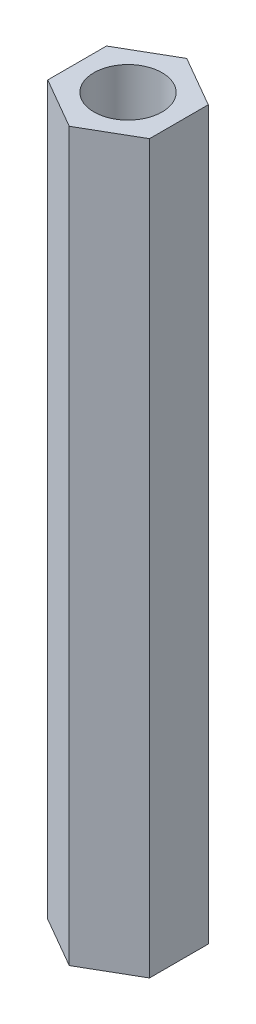
SolidWorks part; units mm, degrees
ref_plane "Front Plane" through (0, 0, 0) normal (0, 0, 1) x (1, 0, 0)
ref_plane "Top Plane" through (0, 0, 0) normal (0, 1, 0) x (1, 0, 0)
ref_plane "Right Plane" through (0, 0, 0) normal (1, 0, 0) x (0, 0, -1)
sketch "Sketch1" plane through (0, 0, 0) normal (0, 1, 0) x (1, 0, 0)
  line L1 (0, -2.0531) -> (1.778, -1.0265)
  line L2 (1.778, -1.0265) -> (1.778, 1.0265)
  line L3 (1.778, 1.0265) -> (0, 2.0531)
  line L4 (0, 2.0531) -> (-1.778, 1.0265)
  line L5 (-1.778, 1.0265) -> (-1.778, -1.0265)
  line L6 (-1.778, -1.0265) -> (0, -2.0531)
  circle A0 centre (0, 0) radius 1.778 construction
  circle A1 centre (0, 0) radius 1.1906
  dimension "D1" = 2.3813
  dimension "D2" = 1.778
extrude "Boss-Extrude1" add sketch "Sketch1" along normal blind 25.4
